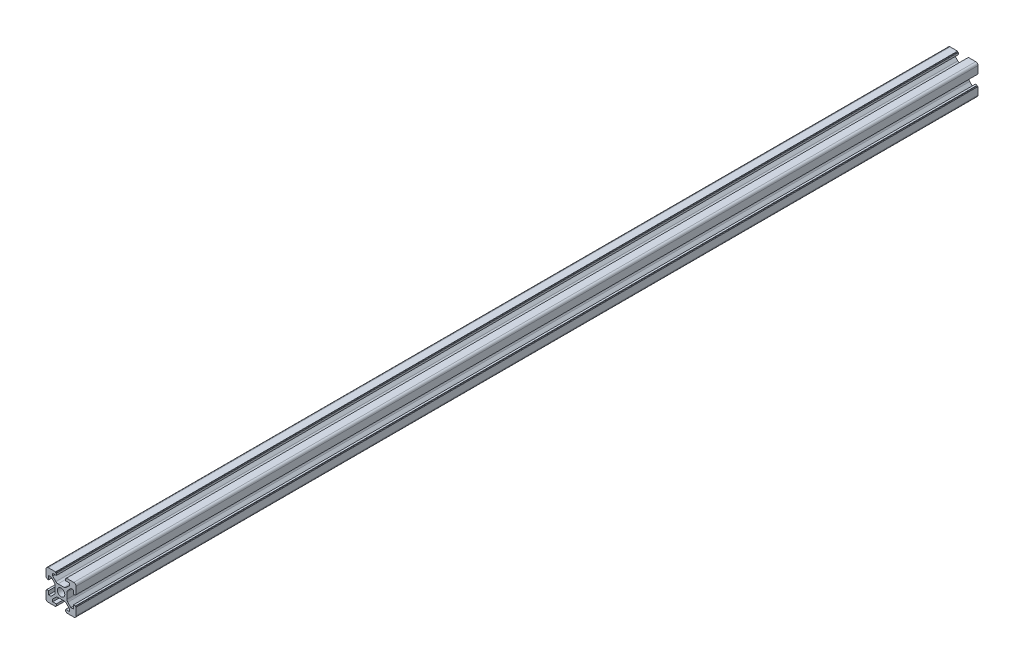
SolidWorks part; units mm, degrees
material "6063-T6"
ref_plane "Спереди" through (0, 0, 0) normal (0, 0, 1) x (1, 0, 0)
ref_plane "Сверху" through (0, 0, 0) normal (0, 1, 0) x (1, 0, 0)
ref_plane "Справа" through (0, 0, 0) normal (1, 0, 0) x (0, 0, -1)
sketch "Sketch1" plane through (0, 0, 0) normal (0, 0, 1) x (1, 0, 0)
  line L0 (0, 10) -> (0, -10) construction
  line L1 (-10, -10) -> (10, -10) construction
  line L2 (-10, -10) -> (-10, 10) construction
  line L3 (-10, 10) -> (10, 10) construction
  line L4 (10, -10) -> (10, 10) construction
  line L5 (-10, -10) -> (10, 10) construction
  line L6 (-10, 10) -> (10, -10) construction
  line L7 (-10, 0) -> (10, 0) construction
  line L8 (0, 3.9) -> (-2.0109, 3.9)
  line L9 (-3.4251, 4.4858) -> (-5.5393, 6.6)
  line L10 (-5.5393, 6.6) -> (-5.5393, 8.2)
  line L11 (-5.5393, 8.2) -> (-3.1, 8.2)
  line L12 (-3.1, 8.2) -> (-3.1, 9.5)
  line L13 (-3.1, 9.5) -> (-3.4, 9.5)
  line L14 (-3.6, 9.7) -> (-3.6, 10)
  line L15 (-3.6, 10) -> (-8.5, 10)
  line L16 (-10, 3.6) -> (-10, 8.5)
  line L17 (-9.7, 3.6) -> (-10, 3.6)
  line L18 (-9.5, 3.1) -> (-9.5, 3.4)
  line L19 (-8.2, 3.1) -> (-9.5, 3.1)
  line L20 (-8.2, 5.5393) -> (-8.2, 3.1)
  line L21 (-6.6, 5.5393) -> (-8.2, 5.5393)
  line L22 (-4.4858, 3.4251) -> (-6.6, 5.5393)
  line L23 (-3.9, 0) -> (-3.9, 2.0109)
  line L24 (3.9, 0) -> (3.9, 2.0109)
  line L25 (4.4858, 3.4251) -> (6.6, 5.5393)
  line L26 (6.6, 5.5393) -> (8.2, 5.5393)
  line L27 (8.2, 5.5393) -> (8.2, 3.1)
  line L28 (8.2, 3.1) -> (9.5, 3.1)
  line L29 (9.5, 3.1) -> (9.5, 3.4)
  line L30 (9.7, 3.6) -> (10, 3.6)
  line L31 (10, 3.6) -> (10, 8.5)
  line L32 (3.6, 10) -> (8.5, 10)
  line L33 (3.6, 9.7) -> (3.6, 10)
  line L34 (3.1, 9.5) -> (3.4, 9.5)
  line L35 (3.1, 8.2) -> (3.1, 9.5)
  line L36 (5.5393, 8.2) -> (3.1, 8.2)
  line L37 (5.5393, 6.6) -> (5.5393, 8.2)
  line L38 (3.4251, 4.4858) -> (5.5393, 6.6)
  line L39 (0, 3.9) -> (2.0109, 3.9)
  line L40 (0, -3.9) -> (2.0109, -3.9)
  line L41 (3.4251, -4.4858) -> (5.5393, -6.6)
  line L42 (5.5393, -6.6) -> (5.5393, -8.2)
  line L43 (5.5393, -8.2) -> (3.1, -8.2)
  line L44 (3.1, -8.2) -> (3.1, -9.5)
  line L45 (3.1, -9.5) -> (3.4, -9.5)
  line L46 (3.6, -9.7) -> (3.6, -10)
  line L47 (3.6, -10) -> (8.5, -10)
  line L48 (10, -3.6) -> (10, -8.5)
  line L49 (9.7, -3.6) -> (10, -3.6)
  line L50 (9.5, -3.1) -> (9.5, -3.4)
  line L51 (8.2, -3.1) -> (9.5, -3.1)
  line L52 (8.2, -5.5393) -> (8.2, -3.1)
  line L53 (6.6, -5.5393) -> (8.2, -5.5393)
  line L54 (4.4858, -3.4251) -> (6.6, -5.5393)
  line L55 (3.9, 0) -> (3.9, -2.0109)
  line L56 (-3.9, 0) -> (-3.9, -2.0109)
  line L57 (-4.4858, -3.4251) -> (-6.6, -5.5393)
  line L58 (-6.6, -5.5393) -> (-8.2, -5.5393)
  line L59 (-8.2, -5.5393) -> (-8.2, -3.1)
  line L60 (-8.2, -3.1) -> (-9.5, -3.1)
  line L61 (-9.5, -3.1) -> (-9.5, -3.4)
  line L62 (-9.7, -3.6) -> (-10, -3.6)
  line L63 (-10, -3.6) -> (-10, -8.5)
  line L64 (-3.6, -10) -> (-8.5, -10)
  line L65 (-3.6, -9.7) -> (-3.6, -10)
  line L66 (-3.1, -9.5) -> (-3.4, -9.5)
  line L67 (-3.1, -8.2) -> (-3.1, -9.5)
  line L68 (-5.5393, -8.2) -> (-3.1, -8.2)
  line L69 (-5.5393, -6.6) -> (-5.5393, -8.2)
  line L70 (-3.4251, -4.4858) -> (-5.5393, -6.6)
  line L71 (0, -3.9) -> (-2.0109, -3.9)
  circle A0 centre (0, 0) radius 2.5
  arc A1 (-8.5, 10) -> (-10, 8.5) centre (-8.5, 8.5) ccw
  arc A2 (-2.0109, 3.9) -> (-3.4251, 4.4858) centre (-2.0109, 5.9) cw
  arc A3 (-3.4, 9.5) -> (-3.6, 9.7) centre (-3.4, 9.7) cw
  arc A4 (-9.5, 3.4) -> (-9.7, 3.6) centre (-9.7, 3.4) ccw
  arc A5 (-3.9, 2.0109) -> (-4.4858, 3.4251) centre (-5.9, 2.0109) ccw
  arc A6 (10, 8.5) -> (8.5, 10) centre (8.5, 8.5) ccw
  arc A7 (3.9, 2.0109) -> (4.4858, 3.4251) centre (5.9, 2.0109) cw
  arc A8 (9.5, 3.4) -> (9.7, 3.6) centre (9.7, 3.4) cw
  arc A9 (3.4, 9.5) -> (3.6, 9.7) centre (3.4, 9.7) ccw
  arc A10 (2.0109, 3.9) -> (3.4251, 4.4858) centre (2.0109, 5.9) ccw
  arc A11 (8.5, -10) -> (10, -8.5) centre (8.5, -8.5) ccw
  arc A12 (2.0109, -3.9) -> (3.4251, -4.4858) centre (2.0109, -5.9) cw
  arc A13 (3.4, -9.5) -> (3.6, -9.7) centre (3.4, -9.7) cw
  arc A14 (9.5, -3.4) -> (9.7, -3.6) centre (9.7, -3.4) ccw
  arc A15 (3.9, -2.0109) -> (4.4858, -3.4251) centre (5.9, -2.0109) ccw
  arc A16 (-10, -8.5) -> (-8.5, -10) centre (-8.5, -8.5) ccw
  arc A17 (-3.9, -2.0109) -> (-4.4858, -3.4251) centre (-5.9, -2.0109) cw
  arc A18 (-9.5, -3.4) -> (-9.7, -3.6) centre (-9.7, -3.4) cw
  arc A19 (-3.4, -9.5) -> (-3.6, -9.7) centre (-3.4, -9.7) ccw
  arc A20 (-2.0109, -3.9) -> (-3.4251, -4.4858) centre (-2.0109, -5.9) ccw
  point P0 (0, 0)
  point P42 (0, 0)
  point P70 (0, 0)
  point P98 (0, 0)
  point P126 (0, 0)
  dimension "D3" = 5
  dimension "D4" = 3
  dimension "D12" = 2
  dimension "D13" = 0.2
  dimension "D1" = 20
  dimension "D2" = 20
  dimension "D5" = 6.2
  dimension "D6" = 7.2
  dimension "D7" = 1.8
  dimension "D8" = 0.5
  dimension "D9" = 3.4
  dimension "D10" = 1.5
  dimension "D11" = 6.1
  dimension "D14" = 4
extrude "Extrude1" add sketch "Sketch1" along normal blind 600
sketch "Szkic1" plane through (10, 0, 0) normal (1, 0, 0) x (0, 0, -1)
  line L0 (0, 3.6) -> (0, -3.6) construction
  line L1 (0, 0) -> (-500, 0) construction
